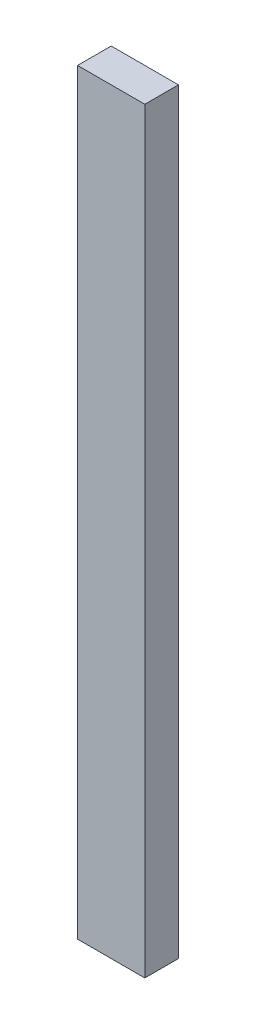
SolidWorks part; units mm, degrees
material "6061 Сплав"
ref_plane "Спереди" through (0, 0, 0) normal (0, 0, 1) x (1, 0, 0)
ref_plane "Сверху" through (0, 0, 0) normal (0, 1, 0) x (1, 0, 0)
ref_plane "Справа" through (0, 0, 0) normal (1, 0, 0) x (0, 0, -1)
sketch "Эскиз1" plane through (0, 0, 0) normal (0, 1, 0) x (1, 0, 0)
  line L1 (0, 0) -> (40, 0)
  line L2 (0, 0) -> (0, 20)
  line L3 (0, 20) -> (40, 20)
  line L4 (40, 0) -> (40, 20)
  dimension "D1" = 20
  dimension "D2" = 40
extrude "Бобышка-Вытянуть1" add sketch "Эскиз1" along normal blind 450
